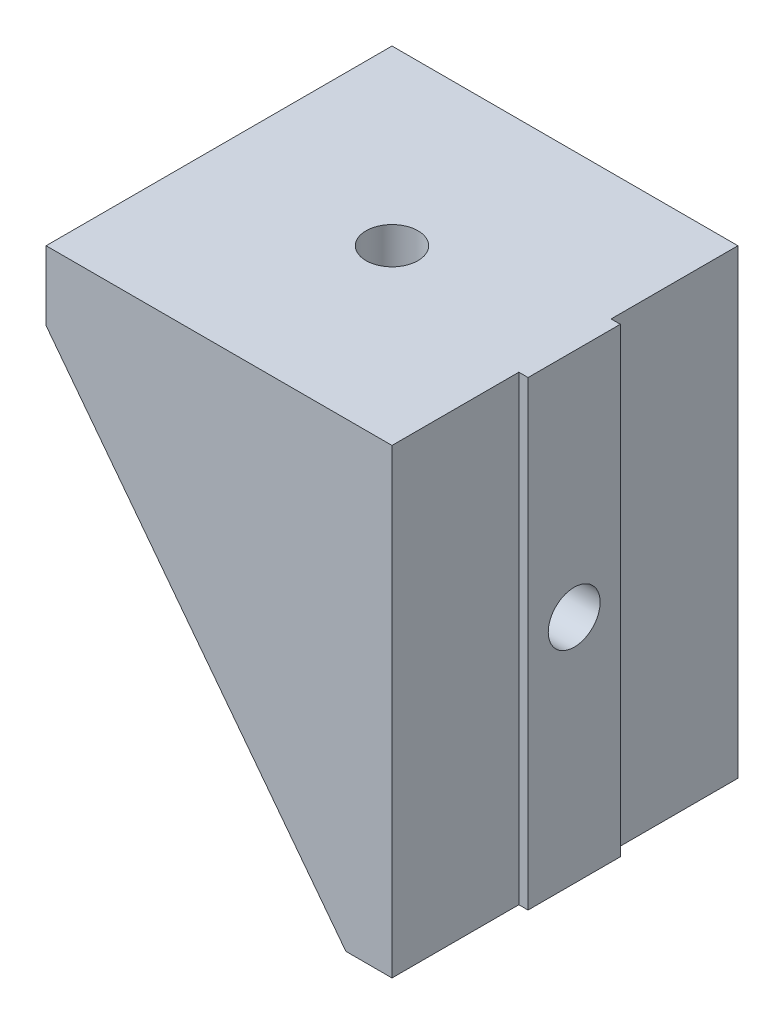
SolidWorks part; units mm, degrees
material "3D printed plastic"
ref_plane "Front Plane" through (0, 0, 0) normal (0, 0, 1) x (1, 0, 0)
ref_plane "Top Plane" through (0, 0, 0) normal (0, 1, 0) x (1, 0, 0)
ref_plane "Right Plane" through (0, 0, 0) normal (1, 0, 0) x (0, 0, -1)
sketch "Sketch1" plane through (0, 0, 0) normal (0, 0, 1) x (1, 0, 0)
  line L0 (0, 0) -> (-30, 0)
  line L1 (-30, 0) -> (-30, -6)
  line L2 (-30, -6) -> (-4, -40)
  line L3 (-4, -40) -> (0, -40)
  line L4 (0, -40) -> (0, 0)
  dimension "D1" = 30
  dimension "D2" = 40
  dimension "D3" = 6
  dimension "D4" = 4
extrude "Boss-Extrude1" add sketch "Sketch1" along normal mid plane 30
sketch "Sketch2" plane through (0, 0, 0) normal (1, 0, 0) x (0, 0, -1)
  line L0 (-15, 0) -> (15, 0) construction
  line L1 (-4, 0) -> (4, 0)
  line L2 (-4, 0) -> (-4, -40)
  line L3 (-4, -40) -> (4, -40)
  line L4 (4, 0) -> (4, -40)
  line L5 (-15, -40) -> (15, -40) construction
  dimension "D1" = 8
extrude "Boss-Extrude2" add sketch "Sketch2" along normal blind 0.8
sketch "Sketch3" plane through (0, 0, 0) normal (0, 0, 1) x (1, 0, 0)
  line L1 (-30, -6) -> (-4, -6)
  line L2 (-30, -6) -> (-30, -40)
  line L3 (-30, -40) -> (-4, -40)
  line L4 (-4, -6) -> (-4, -40)
extrude "Cut-Extrude1" cut sketch "Sketch3" against normal mid plane 20
sketch "Sketch4" plane through (-4, 0, 0) normal (-1, 0, 0) x (0, 0, 1)
  line L0 (0, -20) -> (0, 0) construction
  circle A0 centre (0, -20) radius 2.25
  dimension "D1" = 4.5
  dimension "D2" = 20
extrude "Cut-Extrude2" cut sketch "Sketch4" against normal through all
sketch "Sketch5" plane through (0, 0, 0) normal (0, 1, 0) x (1, 0, 0)
  line L0 (-15, 0) -> (0, 0) construction
  circle A0 centre (-15, 0) radius 2.25
  dimension "D1" = 4.5
  dimension "D2" = 15
extrude "Cut-Extrude3" cut sketch "Sketch5" against normal through all
